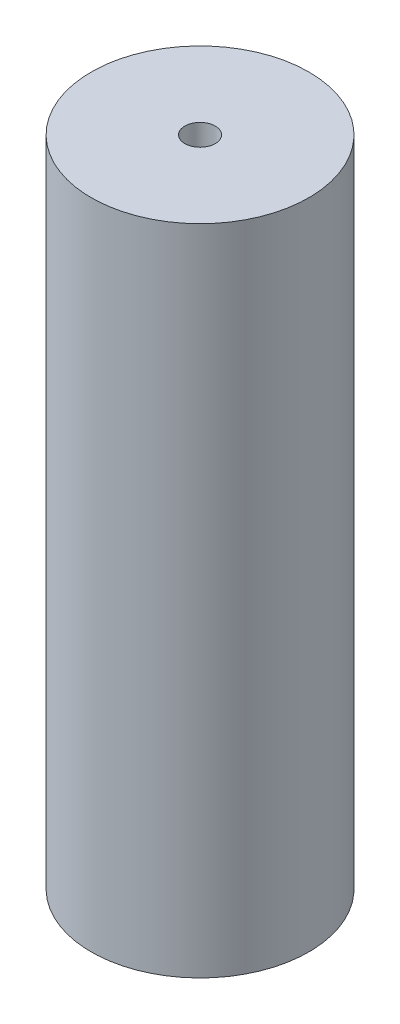
SolidWorks part; units mm, degrees
ref_plane "Front Plane" through (0, 0, 0) normal (0, 0, 1) x (1, 0, 0)
ref_plane "Top Plane" through (0, 0, 0) normal (0, 1, 0) x (1, 0, 0)
ref_plane "Right Plane" through (0, 0, 0) normal (1, 0, 0) x (0, 0, -1)
sketch "Sketch1" plane through (0, 0, 0) normal (0, 0, 1) x (1, 0, 0)
  line L0 (0, 0) -> (0, 5.7533) construction
  line L1 (-0.35, 15) -> (-0.35, 5)
  line L2 (-0.35, 5) -> (-1.25, 5)
  line L3 (-1.25, 5) -> (-1.25, 0)
  line L4 (-1.25, 0) -> (-2.5, 0)
  line L5 (-2.5, 0) -> (-2.5, 15)
  line L6 (-2.5, 15) -> (-0.35, 15)
  dimension "D1" = 2.5
  dimension "D2" = 5
  dimension "D3" = 0.7
  dimension "D4" = 10
  dimension "D5" = 5
revolve "Revolve1" add sketch "Sketch1" angle 360 about L0
